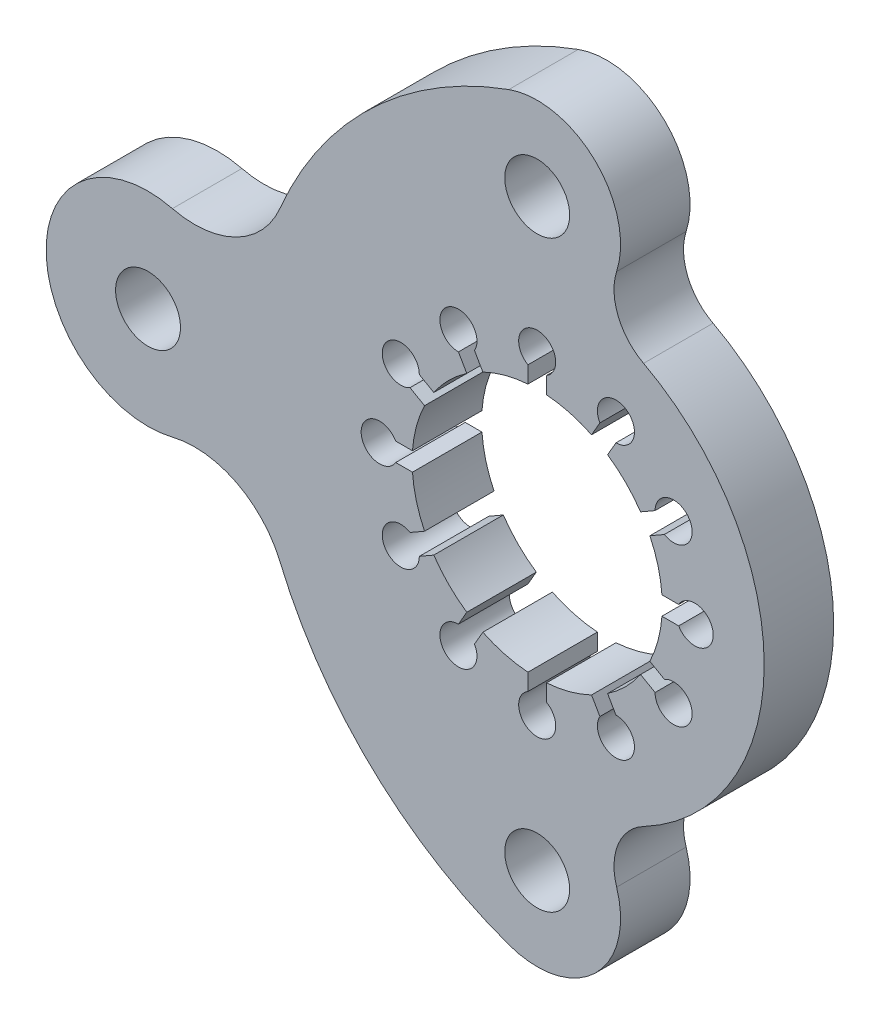
SolidWorks part; units mm, degrees
ref_plane "Alzado" through (0, 0, 0) normal (0, 0, 1) x (1, 0, 0)
ref_plane "Planta" through (0, 0, 0) normal (0, 1, 0) x (1, 0, 0)
ref_plane "Vista lateral" through (0, 0, 0) normal (1, 0, 0) x (0, 0, -1)
sketch "Croquis1" plane through (0, 0, 0) normal (0, 0, 1) x (1, 0, 0)
  line L0 (-17.1588, 0) -> (17.1588, 0) construction
  arc A3 (22.9601, -43.2878) -> (22.9601, 43.2878) centre (0, 0) ccw
  arc A5 (17.1498, 57.5333) -> (-6.1263, 79.9254) centre (0, 63) ccw
  arc A6 (-78.7376, 21.3613) -> (-78.7376, -21.3613) centre (-84, 0) ccw
  arc A9 (17.1498, 57.5333) -> (22.9601, 43.2878) centre (28.583, 53.8889) ccw
  arc A10 (17.1498, -57.5333) -> (22.9601, -43.2878) centre (28.583, -53.8889) cw
  arc A11 (17.1498, -57.5333) -> (-6.1263, -79.9254) centre (0, -63) cw
  arc A12 (-6.1263, 79.9254) -> (-55.5236, 33.013) centre (22.8035, 0) ccw
  arc A13 (-78.7376, 21.3613) -> (-55.5236, 33.013) centre (-73.9536, 40.7807) ccw
  arc A14 (-78.7376, -21.3613) -> (-55.5236, -33.013) centre (-73.9536, -40.7807) cw
  arc A17 (-55.5236, -33.013) -> (-6.1263, -79.9254) centre (22.8035, 0) ccw
  point P11 (0, 0)
  dimension "D1" = 98
  dimension "D2" = 36
  dimension "D3" = 12
  dimension "D4" = 44
  dimension "D5" = 85
  dimension "D6" = 126
  dimension "D8" = 20
  dimension "D9" = 20
  dimension "D7" = 84
extrude "Saliente-Extruir1" add sketch "Croquis1" against normal blind 15
sketch "Croquis2" plane through (0, 0, 0) normal (0, 0, 1) x (1, 0, 0)
  line L0 (-2, 30.5359) -> (-2, 26.9258)
  line L1 (2, 30.5359) -> (2, 26.9258)
  line L2 (17, 25.4449) -> (15.195, 22.3184)
  line L3 (13.5359, 27.4449) -> (11.7309, 24.3184)
  line L4 (27.4449, 13.5359) -> (24.3184, 11.7309)
  line L5 (25.4449, 17) -> (22.3184, 15.195)
  line L6 (30.5359, -2) -> (26.9258, -2)
  line L7 (30.5359, 2) -> (26.9258, 2)
  line L8 (25.4449, -17) -> (22.3184, -15.195)
  line L9 (27.4449, -13.5359) -> (24.3184, -11.7309)
  line L10 (13.5359, -27.4449) -> (11.7309, -24.3184)
  line L11 (17, -25.4449) -> (15.195, -22.3184)
  line L12 (-2, -30.5359) -> (-2, -26.9258)
  line L13 (2, -30.5359) -> (2, -26.9258)
  line L14 (-17, -25.4449) -> (-15.195, -22.3184)
  line L15 (-13.5359, -27.4449) -> (-11.7309, -24.3184)
  line L16 (-27.4449, -13.5359) -> (-24.3184, -11.7309)
  line L17 (-25.4449, -17) -> (-22.3184, -15.195)
  line L18 (-30.5359, 2) -> (-26.9258, 2)
  line L19 (-30.5359, -2) -> (-26.9258, -2)
  line L20 (-25.4449, 17) -> (-22.3184, 15.195)
  line L21 (-27.4449, 13.5359) -> (-24.3184, 11.7309)
  line L22 (-13.5359, 27.4449) -> (-11.7309, 24.3184)
  line L23 (-17, 25.4449) -> (-15.195, 22.3184)
  circle A0 centre (0, 63) radius 7
  circle A1 centre (-84, 0) radius 7
  circle A2 centre (0, -63) radius 7
  circle A3 centre (0, 0) radius 34 construction
  arc A4 (-2, 26.9258) -> (-11.7309, 24.3184) centre (0, 0) ccw
  arc A5 (2, 30.5359) -> (-2, 30.5359) centre (0, 34) ccw
  arc A6 (17, 25.4449) -> (13.5359, 27.4449) centre (17, 29.4449) ccw
  arc A7 (27.4449, 13.5359) -> (25.4449, 17) centre (29.4449, 17) ccw
  arc A8 (30.5359, -2) -> (30.5359, 2) centre (34, 0) ccw
  arc A9 (25.4449, -17) -> (27.4449, -13.5359) centre (29.4449, -17) ccw
  arc A10 (17.1498, 57.5333) -> (22.9601, 43.2878) centre (28.583, 53.8889) ccw
  arc A11 (17.1498, 57.5333) -> (-6.1263, 79.9254) centre (0, 63) ccw
  arc A12 (-6.1263, 79.9254) -> (-55.5236, 33.013) centre (22.8035, 0) ccw
  arc A13 (-78.7376, 21.3613) -> (-55.5236, 33.013) centre (-73.9536, 40.7807) ccw
  arc A14 (-78.7376, 21.3613) -> (-78.7376, -21.3613) centre (-84, 0) ccw
  arc A15 (-55.5236, -33.013) -> (-78.7376, -21.3613) centre (-73.9536, -40.7807) ccw
  arc A16 (-55.5236, -33.013) -> (-6.1263, -79.9254) centre (22.8035, 0) ccw
  arc A17 (-6.1263, -79.9254) -> (17.1498, -57.5333) centre (0, -63) ccw
  arc A18 (22.9601, -43.2878) -> (17.1498, -57.5333) centre (28.583, -53.8889) ccw
  arc A19 (22.9601, -43.2878) -> (22.9601, 43.2878) centre (0, 0) ccw
  arc A20 (17.1498, 57.5333) -> (22.9601, 43.2878) centre (28.583, 53.8889) ccw
  arc A21 (17.1498, 57.5333) -> (-6.1263, 79.9254) centre (0, 63) ccw
  arc A22 (-6.1263, 79.9254) -> (-55.5236, 33.013) centre (22.8035, 0) ccw
  arc A23 (-78.7376, 21.3613) -> (-55.5236, 33.013) centre (-73.9536, 40.7807) ccw
  arc A24 (-78.7376, 21.3613) -> (-78.7376, -21.3613) centre (-84, 0) ccw
  arc A25 (-55.5236, -33.013) -> (-78.7376, -21.3613) centre (-73.9536, -40.7807) ccw
  arc A26 (-55.5236, -33.013) -> (-6.1263, -79.9254) centre (22.8035, 0) ccw
  arc A27 (-6.1263, -79.9254) -> (17.1498, -57.5333) centre (0, -63) ccw
  arc A28 (22.9601, -43.2878) -> (17.1498, -57.5333) centre (28.583, -53.8889) ccw
  arc A29 (22.9601, -43.2878) -> (22.9601, 43.2878) centre (0, 0) ccw
  arc A30 (13.5359, -27.4449) -> (17, -25.4449) centre (17, -29.4449) ccw
  arc A31 (-2, -30.5359) -> (2, -30.5359) centre (0, -34) ccw
  arc A32 (-17, -25.4449) -> (-13.5359, -27.4449) centre (-17, -29.4449) ccw
  arc A33 (-27.4449, -13.5359) -> (-25.4449, -17) centre (-29.4449, -17) ccw
  arc A34 (-30.5359, 2) -> (-30.5359, -2) centre (-34, 0) ccw
  arc A35 (-25.4449, 17) -> (-27.4449, 13.5359) centre (-29.4449, 17) ccw
  arc A36 (-13.5359, 27.4449) -> (-17, 25.4449) centre (-17, 29.4449) ccw
  arc A37 (22.3184, 15.195) -> (15.195, 22.3184) centre (0, 0) ccw
  arc A38 (26.9258, 2) -> (24.3184, 11.7309) centre (0, 0) ccw
  arc A39 (24.3184, -11.7309) -> (26.9258, -2) centre (0, 0) ccw
  arc A40 (11.7309, 24.3184) -> (2, 26.9258) centre (0, 0) ccw
  arc A41 (-15.195, 22.3184) -> (-22.3184, 15.195) centre (0, 0) ccw
  arc A42 (-24.3184, 11.7309) -> (-26.9258, 2) centre (0, 0) ccw
  arc A43 (-26.9258, -2) -> (-24.3184, -11.7309) centre (0, 0) ccw
  arc A44 (-22.3184, -15.195) -> (-15.195, -22.3184) centre (0, 0) ccw
  arc A45 (-11.7309, -24.3184) -> (-2, -26.9258) centre (0, 0) ccw
  arc A46 (2, -26.9258) -> (11.7309, -24.3184) centre (0, 0) ccw
  arc A47 (15.195, -22.3184) -> (22.3184, -15.195) centre (0, 0) ccw
  point P87 (0, 0)
  dimension "D2" = 14
  dimension "D3" = 54
  dimension "D4" = 68
  dimension "D5" = 8
  dimension "D6" = 4
  dimension "D1" = 0
  dimension "D7" = 12
extrude "Cortar-Extruir1" cut sketch "Croquis2" against normal through all contours A0 | A1 | A2 | L0 A4 L22 A36 L23 A41 L20 A35 L21 A42 L18 A34 L19 A43 L16 A33 L17 A44 L14 A32 L15 A45 L12 A31 L13 A46 L10 A30 L11 A47 L8 A9 L9 A39 L6 A8 L7 A38 L4 A7 L5 A37 L2 A6 L3 A40 L1 A5
